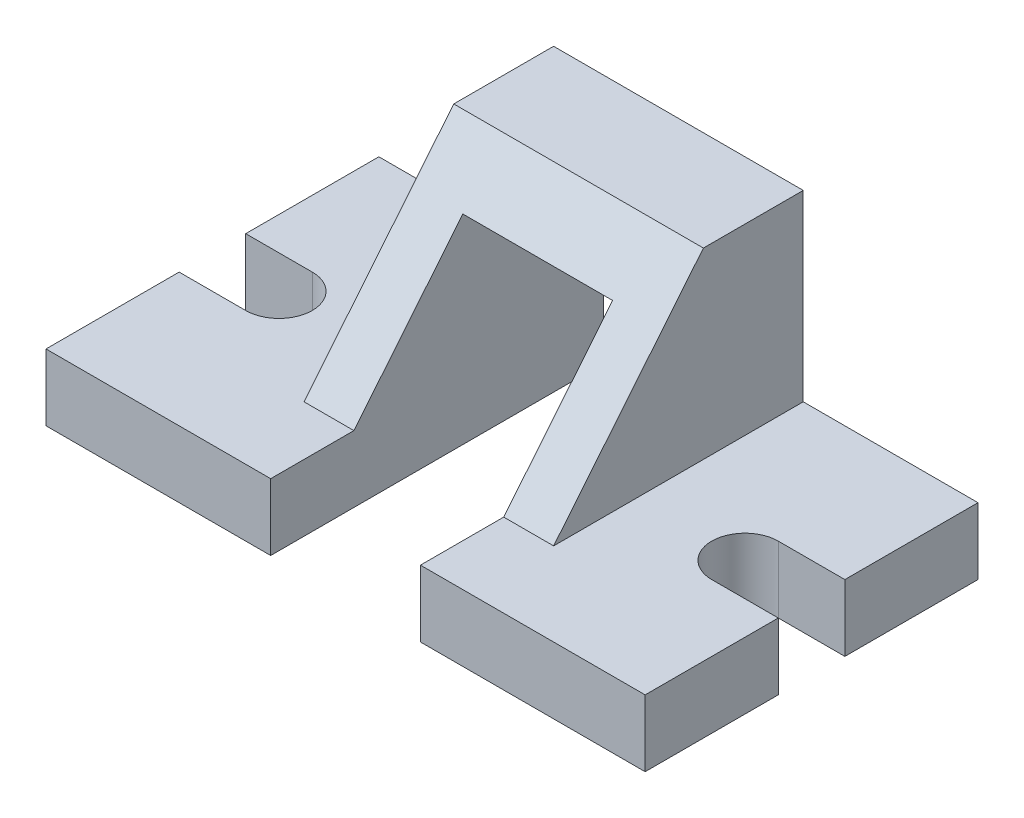
SolidWorks part; units mm, degrees
ref_plane "前视基准面" through (0, 0, 0) normal (0, 0, 1) x (1, 0, 0)
ref_plane "上视基准面" through (0, 0, 0) normal (0, 1, 0) x (1, 0, 0)
ref_plane "右视基准面" through (0, 0, 0) normal (1, 0, 0) x (0, 0, -1)
sketch "草图1" plane through (0, 0, 0) normal (0, 1, 0) x (1, 0, 0)
  line L1 (-36, -20) -> (36, -20)
  line L2 (-36, -20) -> (-36, 20)
  line L3 (-36, 20) -> (36, 20)
  line L4 (36, -20) -> (36, 20)
  line L5 (-36, -20) -> (36, 20) construction
  line L6 (-36, 20) -> (36, -20) construction
  point P0 (0, 0)
extrude "凸台-拉伸1" add sketch "草图1" along normal blind 8
sketch "草图2" plane through (0, 0, 0) normal (0, 1, 0) x (1, 0, 0)
  line L0 (36, 20) -> (-36, 20) construction
  line L1 (-15, -20) -> (15, -20)
  line L2 (-15, -20) -> (-15, 20)
  line L3 (-15, 20) -> (15, 20)
  line L4 (15, -20) -> (15, 20)
  line L5 (-15, -20) -> (15, 20) construction
  line L6 (-15, 20) -> (15, -20) construction
  point P0 (0, 0)
  point P8 (0, 0)
extrude "凸台-拉伸2" add sketch "草图2" along normal blind 30
sketch "草图3" plane through (0, 0, 0) normal (1, 0, 0) x (0, 0, -1)
  line L2 (-20, 8) -> (20, 8) construction
  line L3 (-9.9965, 8) -> (8, 30)
  line L4 (-20, 30) -> (20, 30) construction
  line L6 (8, 30) -> (-20, 30)
  line L7 (-20, 30) -> (-20, 8)
  line L8 (-20, 8) -> (-9.9965, 8)
extrude "切除-拉伸1" cut sketch "草图3" against normal blind 30 and the other way blind 30
sketch "草图4" plane through (0, 0, 0) normal (0, 0, 1) x (1, 0, 0)
  line L0 (-36, 0) -> (36, 0) construction
  line L1 (-9, 0) -> (9, 0)
  line L2 (-9, 0) -> (-9, 24)
  line L3 (-9, 24) -> (9, 24)
  line L4 (9, 0) -> (9, 24)
extrude "切除-拉伸2" cut sketch "草图4" against normal blind 30 and the other way blind 30
sketch "草图7" plane through (0, 0, 0) normal (0, 1, 0) x (1, 0, 0)
  line L0 (-28, 4) -> (-36, 4)
  line L1 (-36, 20) -> (-36, -20) construction
  line L2 (-36, 4) -> (-36, -4)
  line L3 (-36, -4) -> (-28, -4)
  line L4 (28, 4) -> (36, 4)
  line L5 (36, -20) -> (36, 20) construction
  line L6 (36, 4) -> (36, -4)
  line L7 (36, -4) -> (28, -4)
  arc A0 (-28, -4) -> (-28, 4) centre (-28, 0) ccw
  arc A1 (28, 4) -> (28, -4) centre (28, 0) ccw
extrude "切除-拉伸4" cut sketch "草图7" against normal blind 30 and the other way blind 30
